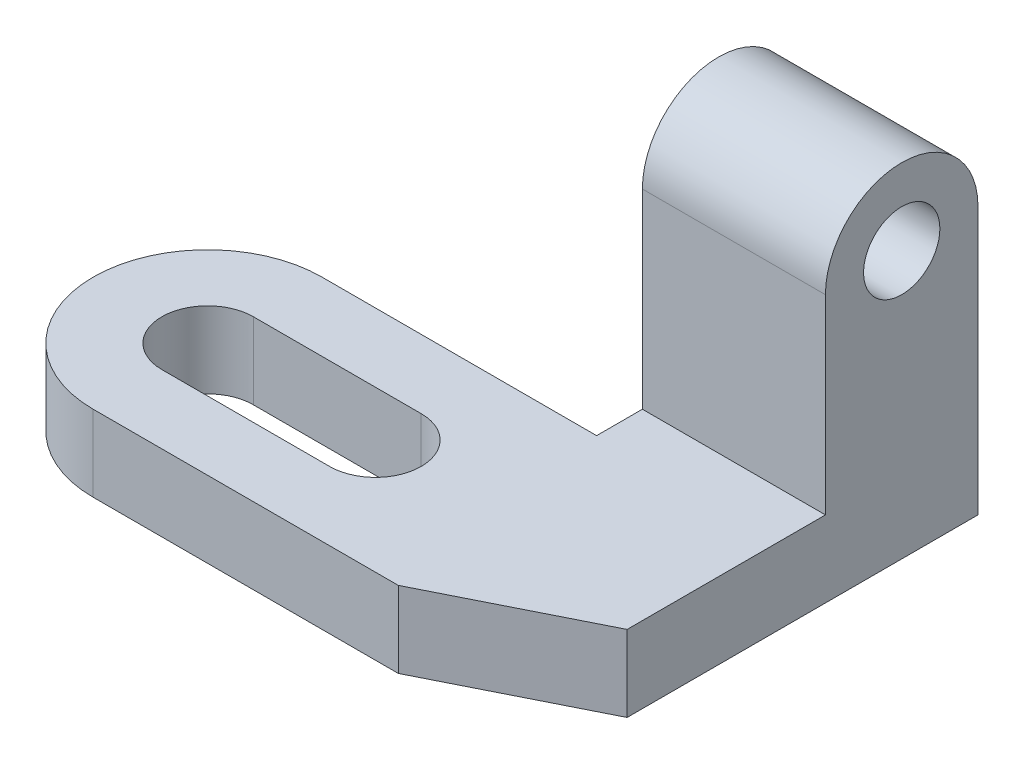
SolidWorks part; units mm, degrees
ref_plane "前视基准面" through (0, 0, 0) normal (0, 0, 1) x (1, 0, 0)
ref_plane "上视基准面" through (0, 0, 0) normal (0, 1, 0) x (1, 0, 0)
ref_plane "右视基准面" through (0, 0, 0) normal (1, 0, 0) x (0, 0, -1)
other "Configuration Table"
sketch "草图1" plane through (0, 0, 0) normal (0, 1, 0) x (1, 0, 0)
  line L0 (0, 0) -> (22, 0) construction
  line L1 (0, 6) -> (22, 6)
  line L2 (0, -6) -> (22, -6)
  line L3 (-305.3125, 0) -> (14960.3144, 0) construction
  line L4 (0, -305.3125) -> (0, 14960.3144) construction
  line L5 (0, 15) -> (36, 15)
  line L6 (36, 15) -> (36, 41)
  line L7 (36, 41) -> (60, 41)
  line L8 (60, 41) -> (60, -5)
  line L9 (60, -5) -> (40, -15)
  line L10 (40, -15) -> (0, -15)
  arc A0 (0, 6) -> (0, -6) centre (0, 0) ccw
  arc A1 (22, -6) -> (22, 6) centre (22, 0) ccw
  arc A2 (0, -15) -> (0, 15) centre (0, 0) cw
  point P2 (11, 0)
  point P20 (0, 0)
  point P21 (-15, 0)
  point P22 (49.9163, -13.9392)
  dimension "D1" = 6
  dimension "D2" = 15
  dimension "D3" = 22
  dimension "D4" = 20
  dimension "D5" = 10
  dimension "D6" = 24
  dimension "D7" = 75
  dimension "D8" = 56
extrude "凸台-拉伸1" add sketch "草图1" along normal blind 10
sketch "草图3" plane through (60, 0, 0) normal (1, 0, 0) x (0, 0, -1)
  line L1 (41, 10) -> (21, 10)
  line L2 (41, 10) -> (41, 35)
  line L4 (21, 10) -> (21, 35)
  circle A0 centre (31, 35) radius 5
  arc A1 (21, 35) -> (41, 35) centre (31, 35) cw
  point P7 (41, 37.6941)
  dimension "D1" = 10
  dimension "D2" = 10
  dimension "D3" = 25
extrude "凸台-拉伸2" add sketch "草图3" against normal up to surface (24 mm away) up to face at (36, 5, -28)
